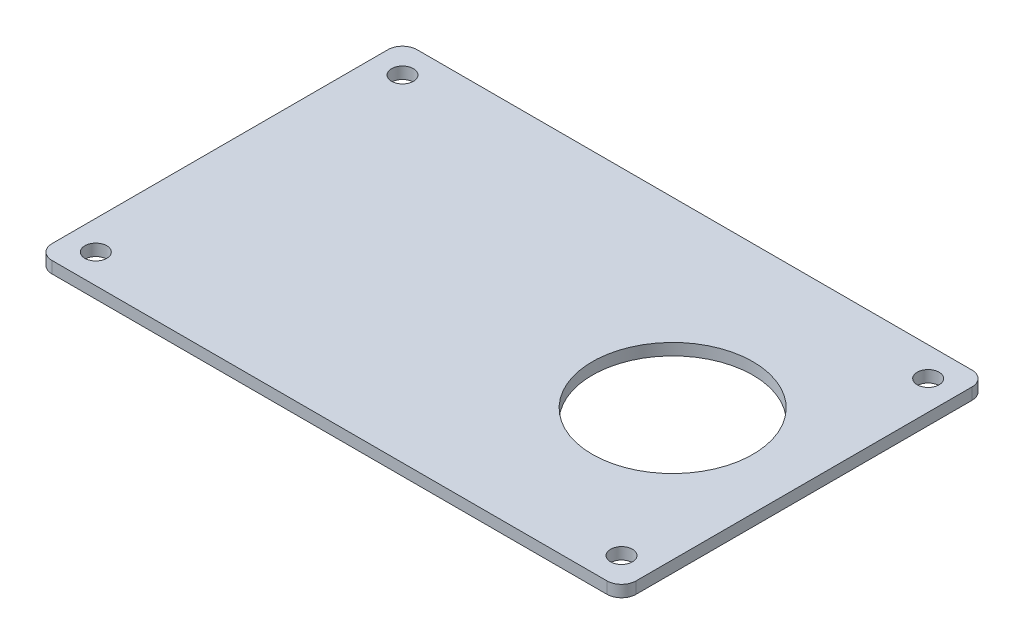
SolidWorks part; units mm, degrees
material "A-玻璃纤维"
ref_plane "前视基准面" through (0, 0, 0) normal (0, 0, 1) x (1, 0, 0)
ref_plane "上视基准面" through (0, 0, 0) normal (0, 1, 0) x (1, 0, 0)
ref_plane "右视基准面" through (0, 0, 0) normal (1, 0, 0) x (0, 0, -1)
other "Configuration Table"
sketch "草图1" plane through (0, 0, 0) normal (0, 1, 0) x (1, 0, 0)
  line L0 (0, 0) -> (0, 33.5742) construction
  line L1 (-40, -25) -> (40, -25)
  line L2 (-40, -25) -> (-40, 25)
  line L3 (-40, 25) -> (40, 25)
  line L4 (40, -25) -> (40, 25)
  line L5 (-40, -25) -> (40, 25) construction
  line L6 (-40, 25) -> (40, -25) construction
  line L7 (0, 0) -> (44.1006, 0) construction
  circle A0 centre (36, 21) radius 1.5
  circle A1 centre (36, -21) radius 1.5
  circle A2 centre (-36, -21) radius 1.5
  circle A3 centre (-36, 21) radius 1.5
  circle A4 centre (22, 0) radius 11
  point P0 (0, 0)
  dimension "D3" = 3
  dimension "D4" = 4
  dimension "D6" = 22
  dimension "D1" = 80
  dimension "D2" = 50
  dimension "D5" = 4
  dimension "D7" = 62
extrude "凸台-拉伸1" add sketch "草图1" along normal blind 1.6
fillet "圆角1" radius 2 4 edges at (-40, 0.8, -25) (-40, 0.8, 25) (40, 0.8, -25) (40, 0.8, 25)
